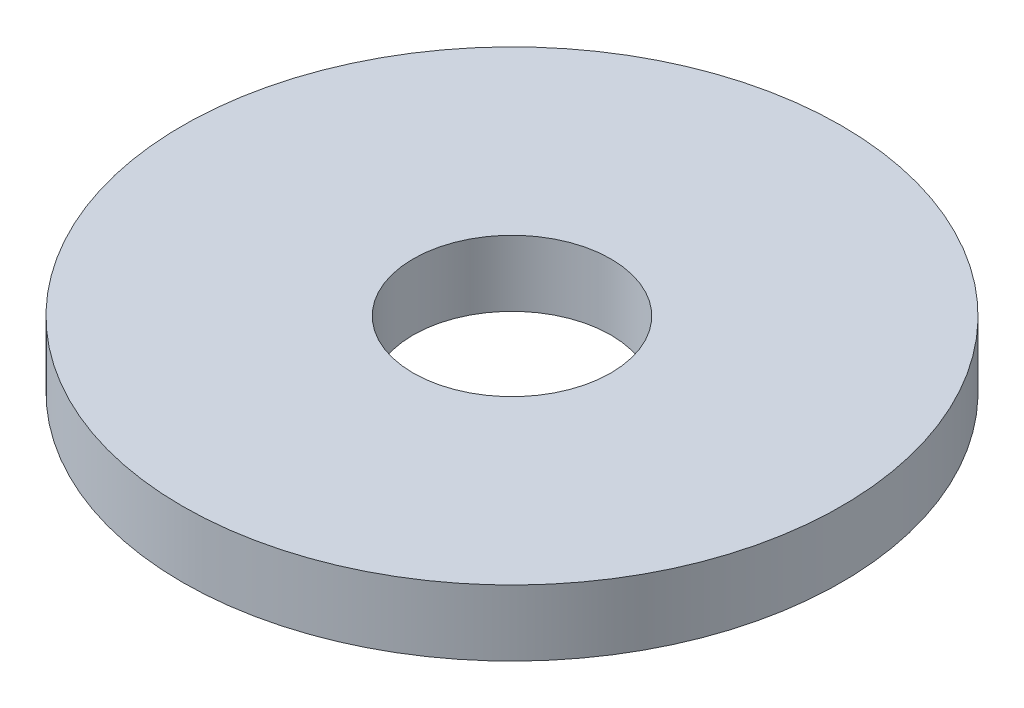
SolidWorks part; units mm, degrees
material "AISI 304"
ref_plane "前视基准面" through (0, 0, 0) normal (0, 0, 1) x (1, 0, 0)
ref_plane "上视基准面" through (0, 0, 0) normal (0, 1, 0) x (1, 0, 0)
ref_plane "右视基准面" through (0, 0, 0) normal (1, 0, 0) x (0, 0, -1)
other "Configuration Table"
sketch "草图1" plane through (0, 0, 0) normal (0, 1, 0) x (1, 0, 0)
  circle A0 centre (0, 0) radius 1.5
  circle A1 centre (0, 0) radius 5
  dimension "D1" = 3
  dimension "D2" = 10
extrude "凸台-拉伸1" add sketch "草图1" along normal blind 1
